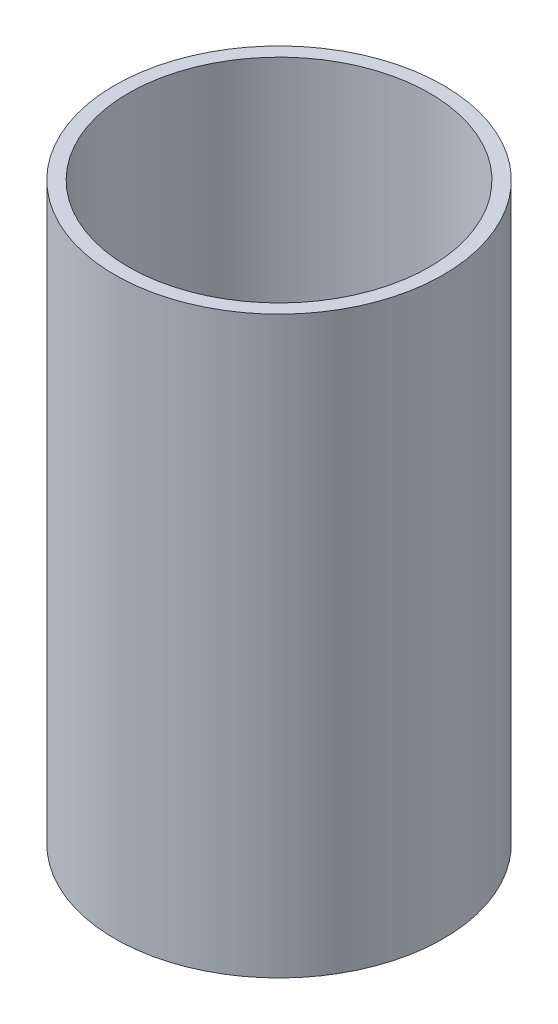
SolidWorks part; units mm, degrees
ref_plane "Front Plane" through (0, 0, 0) normal (0, 0, 1) x (1, 0, 0)
ref_plane "Top Plane" through (0, 0, 0) normal (0, 1, 0) x (1, 0, 0)
ref_plane "Right Plane" through (0, 0, 0) normal (1, 0, 0) x (0, 0, -1)
sketch "Sketch1" plane through (0, 0, 0) normal (0, 1, 0) x (1, 0, 0)
  circle A0 centre (0, 0) radius 12
  dimension "D1" = 24
extrude "Boss-Extrude1" add sketch "Sketch1" along normal blind 42
sketch "Sketch2" plane through (0, 42, 0) normal (0, 1, 0) x (1, 0, 0)
  circle A0 centre (0, 0) radius 11
  dimension "D1" = 22
extrude "Cut-Extrude1" cut sketch "Sketch2" against normal up to next
